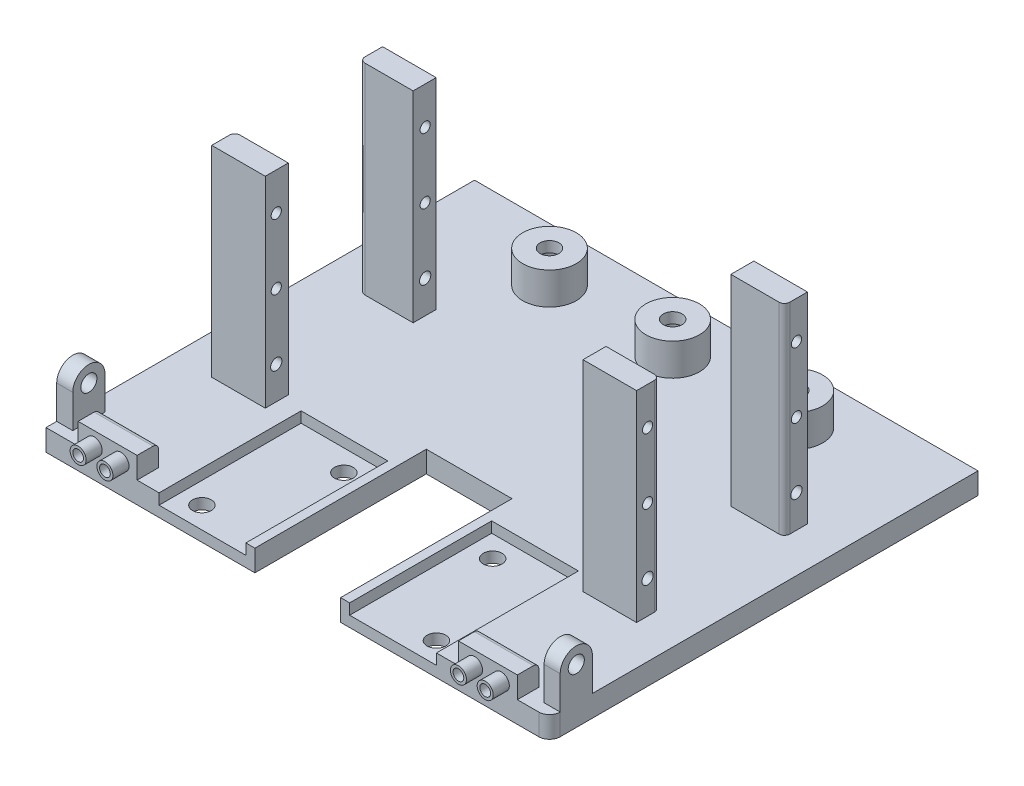
SolidWorks part; units mm, degrees
ref_plane "前视基准面" through (0, 0, 0) normal (0, 0, 1) x (1, 0, 0)
ref_plane "上视基准面" through (0, 0, 0) normal (0, 1, 0) x (1, 0, 0)
ref_plane "右视基准面" through (0, 0, 0) normal (1, 0, 0) x (0, 0, -1)
other "Configuration Table"
sketch "草图1" plane through (0, 0, 0) normal (0, 1, 0) x (1, 0, 0)
  line L1 (-51, -40) -> (51, -40)
  line L2 (-51, -40) -> (-51, 40)
  line L3 (-51, 40) -> (51, 40)
  line L4 (51, -40) -> (51, 40)
  line L5 (-51, -40) -> (51, 40) construction
  line L6 (-51, 40) -> (51, -40) construction
  point P0 (0, 0)
  dimension "D1" = 102
  dimension "D2" = 80
extrude "凸台-拉伸1" add sketch "草图1" along normal blind 4
ref_plane "基准面1" through (44, 0, 0) normal (1, 0, 0) x (0, 0, -1)
sketch "草图5" plane through (44, 0, 0) normal (1, 0, 0) x (0, 0, -1)
  line L0 (-28.0042, 10.2) -> (-28.0042, 4)
  line L1 (-40, 4) -> (40, 4) construction
  line L2 (-28.0042, 4) -> (-21.9958, 4)
  line L3 (-21.9958, 4) -> (-21.9958, 10.2)
  line L5 (-40, 4) -> (-40, 0) construction
  arc A0 (-21.9958, 10.2) -> (-28.0042, 10.2) centre (-25, 10.2) ccw
  circle A1 centre (-25, 10.2) radius 1.505
  dimension "D1" = 3.01
  dimension "D2" = 6.2
  dimension "D3" = 3.0042
  dimension "D4" = 15
extrude "凸台-拉伸3" add sketch "草图5" along normal blind 3
ref_plane "基准面2" through (0, 0, 25) normal (0, 0, -1) x (-1, 0, 0)
mirror "镜向1" about plane through (0, 0, 0) normal (1, 0, 0) of "凸台-拉伸3"
sketch "草图16" plane through (0, 4, 0) normal (0, 1, 0) x (1, 0, 0)
  line L2 (39.46, -2.0001) -> (21.56, -2.0001)
  line L3 (21.56, 21.0999) -> (39.46, 21.0999)
  line L5 (29.66, 25.4999) -> (39.66, 25.4999)
  line L6 (29.66, 25.4999) -> (29.66, 21.1999)
  line L7 (29.66, 21.1999) -> (39.66, 21.1999)
  line L8 (39.66, 25.4999) -> (39.66, 21.1999)
  line L10 (29.66, -6.4001) -> (39.66, -6.4001)
  line L11 (29.66, -6.4001) -> (29.66, -2.1001)
  line L12 (29.66, -2.1001) -> (39.66, -2.1001)
  line L13 (39.66, -6.4001) -> (39.66, -2.1001)
  line L14 (51, 40) -> (-51, 40) construction
  line L15 (-51, -40) -> (51, -40) construction
  line L16 (51, -40) -> (51, 40) construction
  dimension "D1" = 0.1
  dimension "D2" = 10
  dimension "D3" = 4.3
  dimension "D4" = 0.1
  dimension "D5" = 4.3
  dimension "D6" = 10
  dimension "D7" = 14.5001
  dimension "D8" = 33.5999
  dimension "D9" = 11.34
  dimension "D10" = 11.34
extrude "凸台-拉伸6" add sketch "草图16" along normal blind 37.5 contours L10 L13 L12 L11 | L8 L5 L6 L7
fillet "圆角3" radius 1 2 edges at (39.66, 22.75, 2.1001) (39.66, 22.75, -21.1999)
sketch "草图17" plane through (39.66, 0, 0) normal (1, 0, 0) x (0, 0, -1)
  line L1 (-40, 4) -> (40, 4) construction
  line L2 (-6.4001, 41.5) -> (-6.4001, 4) construction
  line L3 (25.4999, 41.5) -> (25.4999, 4) construction
  circle A0 centre (-4.3501, 10.1) radius 1.05
  circle A1 centre (23.4499, 10.1) radius 1.05
  circle A2 centre (23.4499, 22.3) radius 0.95
  circle A3 centre (23.4499, 34.5) radius 0.95
  circle A4 centre (-4.3501, 34.5) radius 0.95
  circle A5 centre (-4.3501, 22.3) radius 0.95
  dimension "D1" = 2.1
  dimension "D2" = 2.1
  dimension "D3" = 1.9
  dimension "D4" = 1.9
  dimension "D5" = 1.9
  dimension "D6" = 1.9
  dimension "D7" = 12.2
  dimension "D8" = 12.2
  dimension "D9" = 6.1
  dimension "D10" = 2.05
  dimension "D12" = 12.2
  dimension "D13" = 6.1
  dimension "D14" = 2.05
  dimension "D11" = 12.2
extrude "切除-拉伸10" cut sketch "草图17" against normal blind 12.5
sketch "草图18" plane through (0, 4, 0) normal (0, 1, 0) x (1, 0, 0)
  line L0 (-51, -40) -> (51, -40) construction
  line L1 (-51, -40) -> (51, -40)
  line L2 (-51, -40) -> (-51, -30)
  line L3 (-51, -30) -> (51, -30)
  line L4 (51, -40) -> (51, -30)
  line L5 (51, -40) -> (51, 40) construction
  line L6 (-51, 40) -> (-51, -40) construction
  dimension "D2" = 10
extrude "切除-拉伸11" cut sketch "草图18" against normal blind 12.5
mirror "镜向2" about plane through (0, 0, 0) normal (1, 0, 0) of "凸台-拉伸6", "圆角3", "切除-拉伸10"
sketch "草图21" plane through (0, 0, 30) normal (0, 0, 1) x (1, 0, 0)
  line L0 (47, 10.2) -> (47, 4) construction
  line L1 (47, 5.3812) -> (52.6366, 5.3812)
  line L2 (47, 5.3812) -> (47, -2.1754)
  line L3 (47, -2.1754) -> (52.6366, -2.1754)
  line L4 (52.6366, 5.3812) -> (52.6366, -2.1754)
extrude "切除-拉伸14" cut sketch "草图21" against normal through all
mirror "镜向5" about plane through (0, 0, 0) normal (1, 0, 0) of "切除-拉伸14"
fillet "圆角7" radius 2 1 edges at (47, 2, 30)
sketch "草图22" plane through (0, 4, 0) normal (0, 1, 0) x (1, 0, 0)
  line L3 (47, -21.9958) -> (47, 40) construction
  line L5 (9.69, -30) -> (9.69, -3.4893)
  line L7 (9.69, -3.4893) -> (25.89, -3.4893)
  line L8 (25.89, -3.4893) -> (25.89, -30)
  line L11 (9.69, -30) -> (25.89, -30)
  line L12 (-47, -21.9958) -> (-47, 40) construction
  line L13 (45, -30) -> (-47, -30) construction
  dimension "D2" = 21.11
  dimension "D3" = 56.69
  dimension "D4" = 26.5107
extrude "切除-拉伸15" cut sketch "草图22" against normal blind 2
sketch "草图23" plane through (0, 2, 0) normal (0, 1, 0) x (1, 0, 0)
  line L4 (9.69, -30) -> (25.89, -30) construction
  line L5 (47, -21.9958) -> (47, 40) construction
  circle A0 centre (13.89, -7.5) radius 1.75
  circle A1 centre (21.89, -26) radius 1.75
  dimension "D1" = 3.5
  dimension "D2" = 3.5
  dimension "D3" = 4
  dimension "D4" = 25.11
  dimension "D5" = 33.11
  dimension "D6" = 22.5
extrude "切除-拉伸16" cut sketch "草图23" against normal through all
mirror "镜向6" about plane through (0, 0, 0) normal (1, 0, 0) of "切除-拉伸16", "切除-拉伸15"
sketch "草图25" plane through (0, 0, 30) normal (0, 0, 1) x (1, 0, 0)
  line L0 (-25.89, 4) -> (-47, 4) construction
  line L1 (-41, 4) -> (-30, 4)
  line L2 (-41, 4) -> (-41, 8)
  line L3 (-41, 8) -> (-30, 8)
  line L4 (-30, 4) -> (-30, 8)
  circle A0 centre (-38, 5.5) radius 1
  circle A1 centre (-33, 5.5) radius 1
  dimension "D1" = 2
  dimension "D2" = 2
  dimension "D4" = 3
  dimension "D5" = 3
  dimension "D6" = 2.5
  dimension "D3" = 5
  dimension "D7" = 4
  dimension "D8" = 30
extrude "凸台-拉伸7" add sketch "草图25" against normal blind 4
sketch "草图27" plane through (0, 0, 30) normal (0, 0, 1) x (1, 0, 0)
  circle A0 centre (-38, 5.5) radius 1.5
  circle A1 centre (-33, 5.5) radius 1.5
  circle A2 centre (-38, 5.5) radius 1 construction
  circle A3 centre (-33, 5.5) radius 1 construction
  circle A4 centre (-38, 5.5) radius 1
  circle A5 centre (-33, 5.5) radius 1
  dimension "D1" = 3
  dimension "D2" = 3
extrude "凸台-拉伸8" add sketch "草图27" along normal blind 3
fillet "圆角8" radius 1 1 edges at (-35.5, 8, 26)
mirror "镜向7" about plane through (0, 0, 0) normal (1, 0, 0) of "凸台-拉伸8", "凸台-拉伸7", "圆角8"
sketch "草图28" plane through (0, 0, 0) normal (0, -1, 0) x (1, 0, 0)
  line L0 (-47, 30) -> (45, 30) construction
  line L1 (-8, 30) -> (8, 30)
  line L2 (-8, 30) -> (-8, -2)
  line L3 (-8, -2) -> (8, -2)
  line L4 (8, 30) -> (8, -2)
  point P4 (0, -2)
  dimension "D1" = 16
  dimension "D2" = 32
extrude "切除-拉伸17" cut sketch "草图28" against normal blind 10
sketch "草图29" plane through (0, 0, -40) normal (0, 0, -1) x (-1, 0, 0)
  line L4 (47, 0) -> (47, 4)
  line L5 (47, 4) -> (-47, 4)
  line L6 (-47, 4) -> (-47, 0)
  line L7 (-47, 0) -> (47, 0)
  line L8 (47, 0) -> (47, 4)
  line L9 (47, 4) -> (-47, 4)
  line L10 (-47, 4) -> (-47, 0)
  line L11 (-47, 0) -> (47, 0)
  dimension "D1" = 0
extrude "凸台-拉伸9" add sketch "草图29" along normal blind 10
sketch "草图30" plane through (0, 0, 0) normal (0, -1, 0) x (1, 0, 0)
  line L0 (47, -50) -> (-47, -50) construction
  line L1 (-47, 30) -> (-47, -50) construction
  circle A3 centre (-23, -40) radius 1.75 construction
  circle A4 centre (0, -40) radius 1.75 construction
  circle A5 centre (23, -40) radius 1.75 construction
  circle A6 centre (-23, -40) radius 5
  circle A7 centre (0, -40) radius 5
  circle A8 centre (23, -40) radius 5
  dimension "D1" = 10
  dimension "D2" = 3.5
  dimension "D3" = 10
  dimension "D7" = 3.5
  dimension "D8" = 3.5
  dimension "D4" = 24
  dimension "D5" = 23
  dimension "D6" = 23
extrude "凸台-拉伸10" add sketch "草图30" against normal blind 10
sketch "草图31" plane through (0, 0, 0) normal (0, -1, 0) x (1, 0, 0)
  circle A3 centre (23, -40) radius 3.5
  circle A4 centre (-23, -40) radius 3.5
  circle A5 centre (0, -40) radius 3.5
  dimension "D1" = 7
extrude "切除-拉伸18" cut sketch "草图31" against normal blind 8
sketch "草图32" plane through (0, 10, 0) normal (0, 1, 0) x (1, 0, 0)
  circle A0 centre (0, 40) radius 1.75
  circle A1 centre (23, 40) radius 1.75
  circle A2 centre (-23, 40) radius 1.75
  dimension "D1" = 3.5
extrude "切除-拉伸19" cut sketch "草图32" against normal blind 8
